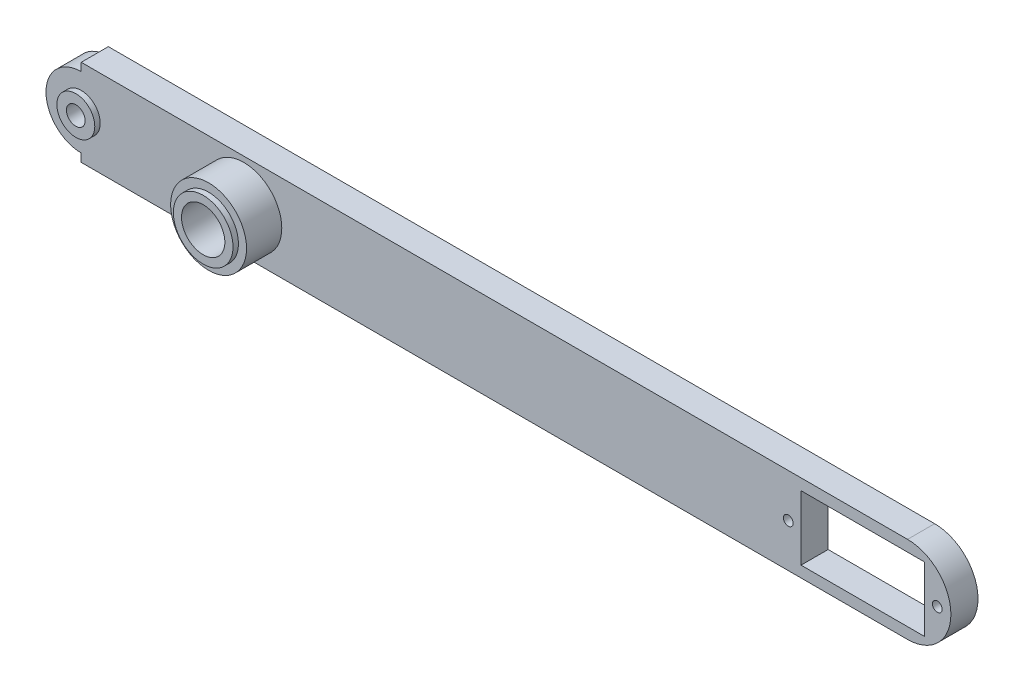
SolidWorks part; units mm, degrees
ref_plane "Front Plane" through (0, 0, 0) normal (0, 0, 1) x (1, 0, 0)
ref_plane "Top Plane" through (0, 0, 0) normal (0, 1, 0) x (1, 0, 0)
ref_plane "Right Plane" through (0, 0, 0) normal (1, 0, 0) x (0, 0, -1)
sketch "Sketch1" plane through (0, 0, 0) normal (0, 0, 1) x (1, 0, 0)
  line L0 (-30, -8) -> (122.45, -8)
  line L1 (122.45, -8) -> (122.45, 8)
  line L2 (122.45, 8) -> (-30, 8)
  line L3 (-30, 8) -> (-30, -8)
extrude "Boss-Extrude1" add sketch "Sketch1" along normal blind 5 from offset 9
sketch "Sketch2" plane through (0, 0, 0) normal (0, 0, 1) x (1, 0, 0)
  circle A0 centre (-30, 0) radius 6.5
extrude "Boss-Extrude2" add sketch "Sketch2" along normal blind 5 from offset 9
sketch "Sketch3" plane through (0, 0, 0) normal (0, 0, 1) x (1, 0, 0)
  circle A0 centre (122.45, 0) radius 8
extrude "Boss-Extrude3" add sketch "Sketch3" along normal blind 5 from offset 9
sketch "Sketch4" plane through (0, 0, 0) normal (0, 0, 1) x (1, 0, 0)
  circle A0 centre (0, 0) radius 7
extrude "Boss-Extrude4" add sketch "Sketch4" along normal blind 11.5 from offset 9
sketch "Sketch5" plane through (0, 0, 0) normal (0, 0, 1) x (1, 0, 0)
  circle A0 centre (0, 0) radius 5.5
extrude "Boss-Extrude5" add sketch "Sketch5" along normal blind 1 from offset 2.5
sketch "Sketch6" plane through (0, 0, 0) normal (0, 0, 1) x (1, 0, 0)
  circle A0 centre (-30, 0) radius 3.5
extrude "Boss-Extrude6" add sketch "Sketch6" along normal blind 1 from offset 4
sketch "Sketch7" plane through (0, 0, 0) normal (0, 0, 1) x (1, 0, 0)
  circle A0 centre (0, 0) radius 4
extrude "Cut-Extrude1" cut sketch "Sketch7" against normal through all and the other way through all
sketch "Sketch8" plane through (0, 0, 0) normal (0, 0, 1) x (1, 0, 0)
  circle A0 centre (-30, 0) radius 1.725
extrude "Cut-Extrude2" cut sketch "Sketch8" against normal through all and the other way through all
sketch "Sketch9" plane through (0, 0, 0) normal (0, 0, 1) x (1, 0, 0)
  line L0 (102.8, -5.95) -> (125.6, -5.95)
  line L1 (125.6, -5.95) -> (125.6, 5.95)
  line L2 (125.6, 5.95) -> (102.8, 5.95)
  line L3 (102.8, 5.95) -> (102.8, -5.95)
extrude "Cut-Extrude3" cut sketch "Sketch9" against normal through all and the other way through all
sketch "Sketch10" plane through (0, 0, 0) normal (0, 0, 1) x (1, 0, 0)
  circle A0 centre (100.45, 0) radius 0.9
  circle A1 centre (127.95, 0) radius 0.9
extrude "Cut-Extrude4" cut sketch "Sketch10" against normal through all and the other way through all
sketch "Sketch11" plane through (0, 0, 0) normal (0, 0, 1) x (1, 0, 0)
  circle A0 centre (40, 0) radius 2
  circle A1 centre (75, 0) radius 2
extrude "Cut-Extrude5" cut sketch "Sketch11" along normal blind 4 from offset 9
